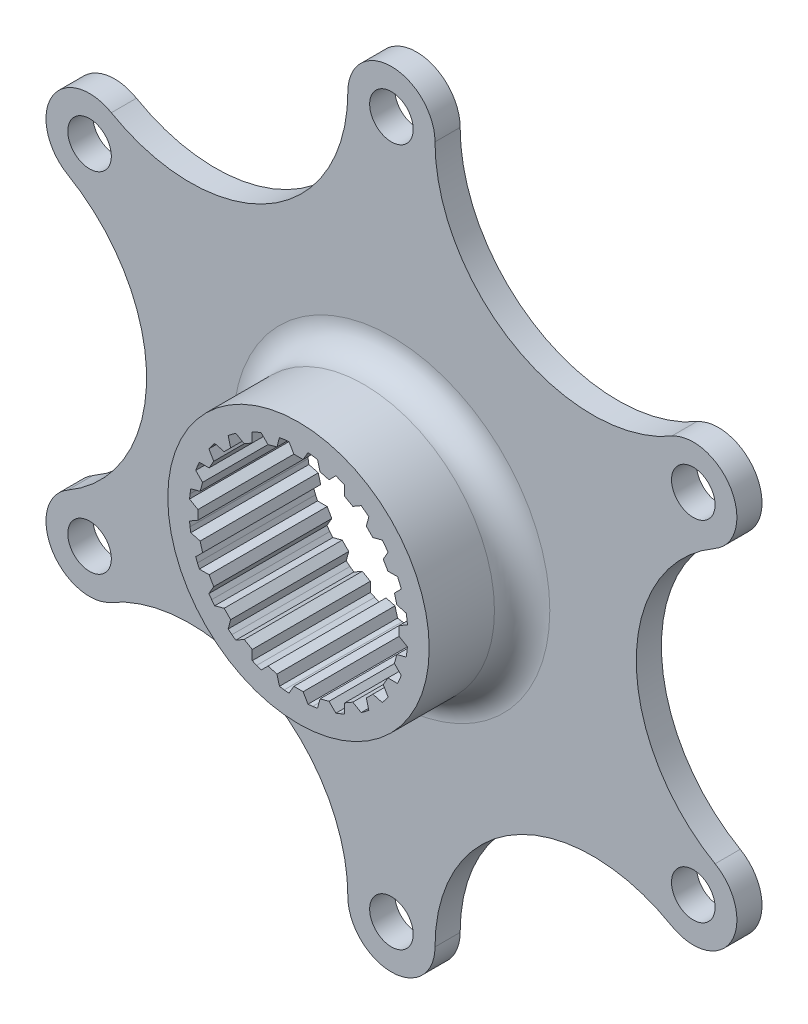
SolidWorks part; units mm, degrees
material "7075-T6 (SN)"
ref_plane "Front Plane" through (0, 0, 0) normal (0, 0, 1) x (1, 0, 0)
ref_plane "Top Plane" through (0, 0, 0) normal (0, 1, 0) x (1, 0, 0)
ref_plane "Right Plane" through (0, 0, 0) normal (1, 0, 0) x (0, 0, -1)
sketch "Sketch1" plane through (0, 0, 0) normal (0, 0, 1) x (1, 0, 0)
  circle A0 centre (0, 0) radius 115
  circle A1 centre (0, 0) radius 95
  circle A2 centre (0, 0) radius 30
  dimension "D1" = 20
  dimension "D3" = 230
extrude "Boss-Extrude1" add sketch "Sketch1" along normal mid plane 27.1 contours A0
sketch "Sketch2" plane through (0, 0, 13.55) normal (0, 0, 1) x (1, 0, 0)
  line L0 (0, 0) -> (0, 37.4359)
  line L1 (1.0655, 23.0754) -> (-1.0655, 23.0754)
  line L2 (-1.0655, 23.0754) -> (-2.1797, 25.0052)
  line L3 (-2.1797, 25.0052) -> (-2.5733, 25.0052)
  line L4 (-2.1797, 25.0052) -> (-3.2762, 24.8853)
  line L5 (1.0655, 23.0754) -> (2.1797, 25.0052)
  line L6 (-4.3664, 24.7173) -> (-3.2762, 24.8853)
  line L7 (2.1797, 25.0052) -> (3.2762, 24.8853)
  line L8 (4.3664, 24.7173) -> (3.2762, 24.8853)
  line L9 (2.1797, 25.0052) -> (3.2762, 24.8853)
  line L10 (4.3664, 24.7173) -> (3.2762, 24.8853)
  line L11 (4.9431, 22.5649) -> (4.3664, 24.7173)
  line L12 (7.0016, 22.0134) -> (4.9431, 22.5649)
  line L13 (7.0016, 22.0134) -> (8.5772, 23.589)
  line L14 (8.5772, 23.589) -> (9.6054, 23.1894)
  line L15 (10.6149, 22.745) -> (9.6054, 23.1894)
  line L16 (8.5772, 23.589) -> (9.6054, 23.1894)
  line L17 (10.6149, 22.745) -> (9.6054, 23.1894)
  line L18 (10.6149, 20.5167) -> (10.6149, 22.745)
  line L19 (12.4605, 19.4511) -> (10.6149, 20.5167)
  line L20 (12.4605, 19.4511) -> (14.3903, 20.5653)
  line L21 (14.3903, 20.5653) -> (15.2799, 19.9132)
  line L22 (16.1401, 19.2226) -> (15.2799, 19.9132)
  line L23 (14.3903, 20.5653) -> (15.2799, 19.9132)
  line L24 (16.1401, 19.2226) -> (15.2799, 19.9132)
  line L25 (15.5633, 17.0702) -> (16.1401, 19.2226)
  line L26 (17.0702, 15.5633) -> (15.5633, 17.0702)
  line L27 (17.0702, 15.5633) -> (19.2226, 16.1401)
  line L28 (19.2226, 16.1401) -> (19.9132, 15.2799)
  line L29 (20.5653, 14.3903) -> (19.9132, 15.2799)
  line L30 (19.2226, 16.1401) -> (19.9132, 15.2799)
  line L31 (20.5653, 14.3903) -> (19.9132, 15.2799)
  line L32 (19.4511, 12.4605) -> (20.5653, 14.3903)
  line L33 (20.5167, 10.6149) -> (19.4511, 12.4605)
  line L34 (20.5167, 10.6149) -> (22.745, 10.6149)
  line L35 (22.745, 10.6149) -> (23.1894, 9.6054)
  line L36 (23.589, 8.5772) -> (23.1894, 9.6054)
  line L37 (22.745, 10.6149) -> (23.1894, 9.6054)
  line L38 (23.589, 8.5772) -> (23.1894, 9.6054)
  line L39 (22.0134, 7.0016) -> (23.589, 8.5772)
  line L40 (22.5649, 4.9431) -> (22.0134, 7.0016)
  line L41 (22.5649, 4.9431) -> (24.7173, 4.3664)
  line L42 (24.7173, 4.3664) -> (24.8853, 3.2762)
  line L43 (25.0052, 2.1797) -> (24.8853, 3.2762)
  line L44 (24.7173, 4.3664) -> (24.8853, 3.2762)
  line L45 (25.0052, 2.1797) -> (24.8853, 3.2762)
  line L46 (23.0754, 1.0655) -> (25.0052, 2.1797)
  line L47 (23.0754, -1.0655) -> (23.0754, 1.0655)
  line L48 (23.0754, -1.0655) -> (25.0052, -2.1797)
  line L49 (25.0052, -2.1797) -> (24.8853, -3.2762)
  line L50 (24.7173, -4.3664) -> (24.8853, -3.2762)
  line L51 (25.0052, -2.1797) -> (24.8853, -3.2762)
  line L52 (24.7173, -4.3664) -> (24.8853, -3.2762)
  line L53 (22.5649, -4.9431) -> (24.7173, -4.3664)
  line L54 (22.0134, -7.0016) -> (22.5649, -4.9431)
  line L55 (22.0134, -7.0016) -> (23.589, -8.5772)
  line L56 (23.589, -8.5772) -> (23.1894, -9.6054)
  line L57 (22.745, -10.6149) -> (23.1894, -9.6054)
  line L58 (23.589, -8.5772) -> (23.1894, -9.6054)
  line L59 (22.745, -10.6149) -> (23.1894, -9.6054)
  line L60 (20.5167, -10.6149) -> (22.745, -10.6149)
  line L61 (19.4511, -12.4605) -> (20.5167, -10.6149)
  line L62 (19.4511, -12.4605) -> (20.5653, -14.3903)
  line L63 (20.5653, -14.3903) -> (19.9132, -15.2799)
  line L64 (19.2226, -16.1401) -> (19.9132, -15.2799)
  line L65 (20.5653, -14.3903) -> (19.9132, -15.2799)
  line L66 (19.2226, -16.1401) -> (19.9132, -15.2799)
  line L67 (17.0702, -15.5633) -> (19.2226, -16.1401)
  line L68 (15.5633, -17.0702) -> (17.0702, -15.5633)
  line L69 (15.5633, -17.0702) -> (16.1401, -19.2226)
  line L70 (16.1401, -19.2226) -> (15.2799, -19.9132)
  line L71 (14.3903, -20.5653) -> (15.2799, -19.9132)
  line L72 (16.1401, -19.2226) -> (15.2799, -19.9132)
  line L73 (14.3903, -20.5653) -> (15.2799, -19.9132)
  line L74 (12.4605, -19.4511) -> (14.3903, -20.5653)
  line L75 (10.6149, -20.5167) -> (12.4605, -19.4511)
  line L76 (10.6149, -20.5167) -> (10.6149, -22.745)
  line L77 (10.6149, -22.745) -> (9.6054, -23.1894)
  line L78 (8.5772, -23.589) -> (9.6054, -23.1894)
  line L79 (10.6149, -22.745) -> (9.6054, -23.1894)
  line L80 (8.5772, -23.589) -> (9.6054, -23.1894)
  line L81 (7.0016, -22.0134) -> (8.5772, -23.589)
  line L82 (4.9431, -22.5649) -> (7.0016, -22.0134)
  line L83 (4.9431, -22.5649) -> (4.3664, -24.7173)
  line L84 (4.3664, -24.7173) -> (3.2762, -24.8853)
  line L85 (2.1797, -25.0052) -> (3.2762, -24.8853)
  line L86 (4.3664, -24.7173) -> (3.2762, -24.8853)
  line L87 (2.1797, -25.0052) -> (3.2762, -24.8853)
  line L88 (1.0655, -23.0754) -> (2.1797, -25.0052)
  line L89 (-1.0655, -23.0754) -> (1.0655, -23.0754)
  line L90 (-1.0655, -23.0754) -> (-2.1797, -25.0052)
  line L91 (-2.1797, -25.0052) -> (-3.2762, -24.8853)
  line L92 (-4.3664, -24.7173) -> (-3.2762, -24.8853)
  line L93 (-2.1797, -25.0052) -> (-3.2762, -24.8853)
  line L94 (-4.3664, -24.7173) -> (-3.2762, -24.8853)
  line L95 (-4.9431, -22.5649) -> (-4.3664, -24.7173)
  line L96 (-7.0016, -22.0134) -> (-4.9431, -22.5649)
  line L97 (-7.0016, -22.0134) -> (-8.5772, -23.589)
  line L98 (-8.5772, -23.589) -> (-9.6054, -23.1894)
  line L99 (-10.6149, -22.745) -> (-9.6054, -23.1894)
  line L100 (-8.5772, -23.589) -> (-9.6054, -23.1894)
  line L101 (-10.6149, -22.745) -> (-9.6054, -23.1894)
  line L102 (-10.6149, -20.5167) -> (-10.6149, -22.745)
  line L103 (-12.4605, -19.4511) -> (-10.6149, -20.5167)
  line L104 (-12.4605, -19.4511) -> (-14.3903, -20.5653)
  line L105 (-14.3903, -20.5653) -> (-15.2799, -19.9132)
  line L106 (-16.1401, -19.2226) -> (-15.2799, -19.9132)
  line L107 (-14.3903, -20.5653) -> (-15.2799, -19.9132)
  line L108 (-16.1401, -19.2226) -> (-15.2799, -19.9132)
  line L109 (-15.5633, -17.0702) -> (-16.1401, -19.2226)
  line L110 (-17.0702, -15.5633) -> (-15.5633, -17.0702)
  line L111 (-17.0702, -15.5633) -> (-19.2226, -16.1401)
  line L112 (-19.2226, -16.1401) -> (-19.9132, -15.2799)
  line L113 (-20.5653, -14.3903) -> (-19.9132, -15.2799)
  line L114 (-19.2226, -16.1401) -> (-19.9132, -15.2799)
  line L115 (-20.5653, -14.3903) -> (-19.9132, -15.2799)
  line L116 (-19.4511, -12.4605) -> (-20.5653, -14.3903)
  line L117 (-20.5167, -10.6149) -> (-19.4511, -12.4605)
  line L118 (-20.5167, -10.6149) -> (-22.745, -10.6149)
  line L119 (-22.745, -10.6149) -> (-23.1894, -9.6054)
  line L120 (-23.589, -8.5772) -> (-23.1894, -9.6054)
  line L121 (-22.745, -10.6149) -> (-23.1894, -9.6054)
  line L122 (-23.589, -8.5772) -> (-23.1894, -9.6054)
  line L123 (-22.0134, -7.0016) -> (-23.589, -8.5772)
  line L124 (-22.5649, -4.9431) -> (-22.0134, -7.0016)
  line L125 (-22.5649, -4.9431) -> (-24.7173, -4.3664)
  line L126 (-24.7173, -4.3664) -> (-24.8853, -3.2762)
  line L127 (-25.0052, -2.1797) -> (-24.8853, -3.2762)
  line L128 (-24.7173, -4.3664) -> (-24.8853, -3.2762)
  line L129 (-25.0052, -2.1797) -> (-24.8853, -3.2762)
  line L130 (-23.0754, -1.0655) -> (-25.0052, -2.1797)
  line L131 (-23.0754, 1.0655) -> (-23.0754, -1.0655)
  line L132 (-23.0754, 1.0655) -> (-25.0052, 2.1797)
  line L133 (-25.0052, 2.1797) -> (-24.8853, 3.2762)
  line L134 (-24.7173, 4.3664) -> (-24.8853, 3.2762)
  line L135 (-25.0052, 2.1797) -> (-24.8853, 3.2762)
  line L136 (-24.7173, 4.3664) -> (-24.8853, 3.2762)
  line L137 (-22.5649, 4.9431) -> (-24.7173, 4.3664)
  line L138 (-22.0134, 7.0016) -> (-22.5649, 4.9431)
  line L139 (-22.0134, 7.0016) -> (-23.589, 8.5772)
  line L140 (-23.589, 8.5772) -> (-23.1894, 9.6054)
  line L141 (-22.745, 10.6149) -> (-23.1894, 9.6054)
  line L142 (-23.589, 8.5772) -> (-23.1894, 9.6054)
  line L143 (-22.745, 10.6149) -> (-23.1894, 9.6054)
  line L144 (-20.5167, 10.6149) -> (-22.745, 10.6149)
  line L145 (-19.4511, 12.4605) -> (-20.5167, 10.6149)
  line L146 (-19.4511, 12.4605) -> (-20.5653, 14.3903)
  line L147 (-20.5653, 14.3903) -> (-19.9132, 15.2799)
  line L148 (-19.2226, 16.1401) -> (-19.9132, 15.2799)
  line L149 (-20.5653, 14.3903) -> (-19.9132, 15.2799)
  line L150 (-19.2226, 16.1401) -> (-19.9132, 15.2799)
  line L151 (-17.0702, 15.5633) -> (-19.2226, 16.1401)
  line L152 (-15.5633, 17.0702) -> (-17.0702, 15.5633)
  line L153 (-15.5633, 17.0702) -> (-16.1401, 19.2226)
  line L154 (-16.1401, 19.2226) -> (-15.2799, 19.9132)
  line L155 (-14.3903, 20.5653) -> (-15.2799, 19.9132)
  line L156 (-16.1401, 19.2226) -> (-15.2799, 19.9132)
  line L157 (-14.3903, 20.5653) -> (-15.2799, 19.9132)
  line L158 (-12.4605, 19.4511) -> (-14.3903, 20.5653)
  line L159 (-10.6149, 20.5167) -> (-12.4605, 19.4511)
  line L160 (-10.6149, 20.5167) -> (-10.6149, 22.745)
  line L161 (-10.6149, 22.745) -> (-9.6054, 23.1894)
  line L162 (-8.5772, 23.589) -> (-9.6054, 23.1894)
  line L163 (-10.6149, 22.745) -> (-9.6054, 23.1894)
  line L164 (-8.5772, 23.589) -> (-9.6054, 23.1894)
  line L165 (-7.0016, 22.0134) -> (-8.5772, 23.589)
  line L166 (-4.9431, 22.5649) -> (-7.0016, 22.0134)
  line L167 (-4.9431, 22.5649) -> (-4.3664, 24.7173)
  line L168 (-4.3664, 24.7173) -> (-3.2762, 24.8853)
  line L169 (-2.1797, 25.0052) -> (-3.2762, 24.8853)
  circle A0 centre (0, 0) radius 80
  circle A1 centre (0, 0) radius 25.1 construction
  circle A2 centre (0, 0) radius 23.0754 construction
  point P13 (0, 23.0754)
  dimension "D1" = 1.0655
  dimension "D2" = 46.1508
  dimension "D3" = 50.2
  dimension "D4" = 60
  dimension "D5" = 2.2283
  dimension "D6" = 6.241
  dimension "D7" = 24
extrude "Cut-Extrude1" cut sketch "Sketch2" against normal through all contours L167 L166 L165 L162 L161 L160 L159 L158 L155 L154 L153 L152 L151 L148 L147 L146 L145 L144 L141 L140 L139 L138 L137 L134 L133 L132 L131 L130 L127 L126 L125 L124 L123 L120 L119 L118 L117 L116 L113 L112 L111 L110 L109 L106 L105 L104 L103 L102 L99 L98 L97
sketch "Sketch3" plane through (0, 0, 13.55) normal (0, 0, 1) x (1, 0, 0)
  circle A0 centre (0, 0) radius 95
  circle A2 centre (0, 0) radius 30
  circle A3 centre (0, 0) radius 95 construction
extrude "Cut-Extrude13" cut sketch "Sketch3" against normal blind 16.06
fillet "Fillet1" radius 6.35 1 edges at (30, 0, -2.51)
ref_plane "Plane1" through (0, 0, -13.55) normal (0, 0, -1) x (-1, 0, 0)
sketch "Sketch7" plane through (0, 0, -13.55) normal (0, 0, -1) x (-1, 0, 0)
  circle A0 centre (0, 0) radius 30
  circle A1 centre (0, 0) radius 95
  circle A2 centre (0, 0) radius 95 construction
extrude "Cut-Extrude14" cut sketch "Sketch7" against normal blind 5.27
fillet "Fillet2" [suppressed] radius 3.175
sketch "Sketch8" plane through (0, 0, -13.55) normal (0, 0, -1) x (-1, 0, 0)
  line L0 (0, 0) -> (-113.4958, 0)
  circle A0 centre (0, 0) radius 95
  circle A1 centre (0, 0) radius 115
  circle A3 centre (-80, 0) radius 3.97
  circle A4 centre (-40, 69.282) radius 3.97
  circle A5 centre (40, 69.282) radius 3.97
  circle A6 centre (80, 0) radius 3.97
  circle A7 centre (40, -69.282) radius 3.97
  circle A8 centre (-40, -69.282) radius 3.97
  circle A9 centre (0, 0) radius 80 construction
  circle A10 centre (0, 0) radius 115 construction
  circle A11 centre (0, 0) radius 95 construction
  dimension "D1" = 6
  dimension "D2" = 160
extrude "Cut-Extrude17" cut sketch "Sketch8" against normal through all contours A0 | A1
sketch "Sketch9" plane through (0, 0, -13.55) normal (0, 0, -1) x (-1, 0, 0)
  line L0 (0, 0) -> (0, 112.897) construction
  circle A0 centre (0, 80) radius 5
  circle A1 centre (0, 0) radius 95
  circle A2 centre (0, 0) radius 95
  circle A3 centre (69.282, 40) radius 5
  circle A4 centre (69.282, -40) radius 5
  circle A5 centre (0, -80) radius 5
  circle A6 centre (-69.282, -40) radius 5
  circle A7 centre (-69.282, 40) radius 5
  point P18 (0, 0)
  dimension "D2" = 10
  dimension "D4" = 80
  dimension "D1" = 0
  dimension "D3" = 6
extrude "Cut-Extrude20" cut sketch "Sketch9" against normal through all contours A6 | A5 | A4 | A3 | A0 | A7
sketch "Sketch10" plane through (0, 0, -13.55) normal (0, 0, -1) x (-1, 0, 0)
  line L0 (-77.9423, -45) -> (-60.6218, -35) construction
  line L1 (-74.282, -31.3397) -> (-64.282, -48.6603) construction
  line L2 (0, -90) -> (0, -70) construction
  line L3 (-10, -80) -> (10, -80) construction
  line L4 (-77.9423, 45) -> (-60.6218, 35) construction
  line L5 (-64.282, 48.6603) -> (-74.282, 31.3397) construction
  line L6 (0, 90) -> (0, 70) construction
  line L7 (10, 80) -> (-10, 80) construction
  line L8 (77.9423, 45) -> (60.6218, 35) construction
  line L9 (74.282, 31.3397) -> (64.282, 48.6603) construction
  line L10 (77.9423, -45) -> (60.6218, -35) construction
  line L11 (64.282, -48.6603) -> (74.282, -31.3397) construction
  circle A0 centre (-69.282, -40) radius 5 construction
  circle A1 centre (0, -80) radius 5 construction
  circle A2 centre (69.282, -40) radius 5 construction
  circle A3 centre (69.282, 40) radius 5 construction
  circle A4 centre (0, 80) radius 5 construction
  circle A5 centre (-69.282, 40) radius 5 construction
  circle A6 centre (-69.282, -40) radius 5
  circle A7 centre (0, -80) radius 5
  circle A8 centre (69.282, -40) radius 5
  circle A9 centre (69.282, 40) radius 5
  circle A10 centre (0, 80) radius 5
  circle A11 centre (-69.282, 40) radius 5
  circle A12 centre (-69.282, 40) radius 10
  circle A13 centre (0, 80) radius 10
  circle A14 centre (69.282, 40) radius 10
  circle A15 centre (69.282, -40) radius 10
  circle A16 centre (0, -80) radius 10
  circle A17 centre (-69.282, -40) radius 10
  arc A18 (-64.282, 48.6603) -> (-10, 80) centre (-46.188, 80) ccw
  arc A19 (10, 80) -> (64.282, 48.6603) centre (46.188, 80) ccw
  arc A20 (74.282, 31.3397) -> (74.282, -31.3397) centre (92.376, 0) ccw
  arc A21 (64.282, -48.6603) -> (10, -80) centre (46.188, -80) ccw
  arc A22 (-10, -80) -> (-64.282, -48.6603) centre (-46.188, -80) ccw
  arc A23 (-74.282, -31.3397) -> (-74.282, 31.3397) centre (-92.376, 0) ccw
  circle A24 centre (0, 0) radius 95 construction
  circle A25 centre (0, 0) radius 95
  point P50 (0, 0)
  point P68 (0, 0)
  dimension "D1" = 20
  dimension "D2" = 20
  dimension "D3" = 20
  dimension "D4" = 20
  dimension "D5" = 20
  dimension "D6" = 20
  dimension "D8" = 6
  dimension "D7" = 6
extrude "Cut-Extrude21" cut sketch "Sketch10" against normal through all
sketch "Sketch11" plane through (0, 0, -13.55) normal (0, 0, -1) x (-1, 0, 0)
  circle A0 centre (0, 0) radius 30
  circle A1 centre (0, 0) radius 30 construction
extrude "Cut-Extrude22" cut sketch "Sketch11" against normal up to surface (5.27 mm away) up to face at (-30, 0, -8.28)
sketch "Sketch13" plane through (0, 0, 13.55) normal (0, 0, 1) x (1, 0, 0)
  line L120 (1.0655, 23.0754) -> (-1.0655, 23.0754)
  line L121 (2.1797, 25.0052) -> (1.0655, 23.0754)
  line L122 (3.2762, 24.8853) -> (2.1797, 25.0052)
  line L123 (4.3664, 24.7173) -> (3.2762, 24.8853)
  line L124 (4.9431, 22.5649) -> (4.3664, 24.7173)
  line L125 (7.0016, 22.0134) -> (4.9431, 22.5649)
  line L126 (8.5772, 23.589) -> (7.0016, 22.0134)
  line L127 (9.6054, 23.1894) -> (8.5772, 23.589)
  line L128 (10.6149, 22.745) -> (9.6054, 23.1894)
  line L129 (10.6149, 20.5167) -> (10.6149, 22.745)
  line L130 (12.4605, 19.4511) -> (10.6149, 20.5167)
  line L131 (14.3903, 20.5653) -> (12.4605, 19.4511)
  line L132 (15.2799, 19.9132) -> (14.3903, 20.5653)
  line L133 (16.1401, 19.2226) -> (15.2799, 19.9132)
  line L134 (15.5633, 17.0702) -> (16.1401, 19.2226)
  line L135 (17.0702, 15.5633) -> (15.5633, 17.0702)
  line L136 (19.2226, 16.1401) -> (17.0702, 15.5633)
  line L137 (19.9132, 15.2799) -> (19.2226, 16.1401)
  line L138 (20.5653, 14.3903) -> (19.9132, 15.2799)
  line L139 (19.4511, 12.4605) -> (20.5653, 14.3903)
  line L140 (20.5167, 10.6149) -> (19.4511, 12.4605)
  line L141 (22.745, 10.6149) -> (20.5167, 10.6149)
  line L142 (23.1894, 9.6054) -> (22.745, 10.6149)
  line L143 (23.589, 8.5772) -> (23.1894, 9.6054)
  line L144 (22.0134, 7.0016) -> (23.589, 8.5772)
  line L145 (22.5649, 4.9431) -> (22.0134, 7.0016)
  line L146 (24.7173, 4.3664) -> (22.5649, 4.9431)
  line L147 (24.8853, 3.2762) -> (24.7173, 4.3664)
  line L148 (25.0052, 2.1797) -> (24.8853, 3.2762)
  line L149 (23.0754, 1.0655) -> (25.0052, 2.1797)
  line L150 (23.0754, -1.0655) -> (23.0754, 1.0655)
  line L151 (25.0052, -2.1797) -> (23.0754, -1.0655)
  line L152 (24.8853, -3.2762) -> (25.0052, -2.1797)
  line L153 (24.7173, -4.3664) -> (24.8853, -3.2762)
  line L154 (22.5649, -4.9431) -> (24.7173, -4.3664)
  line L155 (22.0134, -7.0016) -> (22.5649, -4.9431)
  line L156 (23.589, -8.5772) -> (22.0134, -7.0016)
  line L157 (23.1894, -9.6054) -> (23.589, -8.5772)
  line L158 (22.745, -10.6149) -> (23.1894, -9.6054)
  line L159 (20.5167, -10.6149) -> (22.745, -10.6149)
  line L160 (19.4511, -12.4605) -> (20.5167, -10.6149)
  line L161 (20.5653, -14.3903) -> (19.4511, -12.4605)
  line L162 (19.9132, -15.2799) -> (20.5653, -14.3903)
  line L163 (19.2226, -16.1401) -> (19.9132, -15.2799)
  line L164 (17.0702, -15.5633) -> (19.2226, -16.1401)
  line L165 (15.5633, -17.0702) -> (17.0702, -15.5633)
  line L166 (16.1401, -19.2226) -> (15.5633, -17.0702)
  line L167 (15.2799, -19.9132) -> (16.1401, -19.2226)
  line L168 (14.3903, -20.5653) -> (15.2799, -19.9132)
  line L169 (12.4605, -19.4511) -> (14.3903, -20.5653)
  line L170 (10.6149, -20.5167) -> (12.4605, -19.4511)
  line L171 (10.6149, -22.745) -> (10.6149, -20.5167)
  line L172 (9.6054, -23.1894) -> (10.6149, -22.745)
  line L173 (8.5772, -23.589) -> (9.6054, -23.1894)
  line L174 (7.0016, -22.0134) -> (8.5772, -23.589)
  line L175 (4.9431, -22.5649) -> (7.0016, -22.0134)
  line L176 (4.3664, -24.7173) -> (4.9431, -22.5649)
  line L177 (3.2762, -24.8853) -> (4.3664, -24.7173)
  line L178 (2.1797, -25.0052) -> (3.2762, -24.8853)
  line L179 (1.0655, -23.0754) -> (2.1797, -25.0052)
  line L180 (-1.0655, -23.0754) -> (1.0655, -23.0754)
  line L181 (-2.1797, -25.0052) -> (-1.0655, -23.0754)
  line L182 (-3.2762, -24.8853) -> (-2.1797, -25.0052)
  line L183 (-4.3664, -24.7173) -> (-3.2762, -24.8853)
  line L184 (-4.9431, -22.5649) -> (-4.3664, -24.7173)
  line L185 (-7.0016, -22.0134) -> (-4.9431, -22.5649)
  line L186 (-8.5772, -23.589) -> (-7.0016, -22.0134)
  line L187 (-9.6054, -23.1894) -> (-8.5772, -23.589)
  line L188 (-10.6149, -22.745) -> (-9.6054, -23.1894)
  line L189 (-10.6149, -20.5167) -> (-10.6149, -22.745)
  line L190 (-12.4605, -19.4511) -> (-10.6149, -20.5167)
  line L191 (-14.3903, -20.5653) -> (-12.4605, -19.4511)
  line L192 (-15.2799, -19.9132) -> (-14.3903, -20.5653)
  line L193 (-16.1401, -19.2226) -> (-15.2799, -19.9132)
  line L194 (-15.5633, -17.0702) -> (-16.1401, -19.2226)
  line L195 (-17.0702, -15.5633) -> (-15.5633, -17.0702)
  line L196 (-19.2226, -16.1401) -> (-17.0702, -15.5633)
  line L197 (-19.9132, -15.2799) -> (-19.2226, -16.1401)
  line L198 (-20.5653, -14.3903) -> (-19.9132, -15.2799)
  line L199 (-19.4511, -12.4605) -> (-20.5653, -14.3903)
  line L200 (-20.5167, -10.6149) -> (-19.4511, -12.4605)
  line L201 (-22.745, -10.6149) -> (-20.5167, -10.6149)
  line L202 (-23.1894, -9.6054) -> (-22.745, -10.6149)
  line L203 (-23.589, -8.5772) -> (-23.1894, -9.6054)
  line L204 (-22.0134, -7.0016) -> (-23.589, -8.5772)
  line L205 (-22.5649, -4.9431) -> (-22.0134, -7.0016)
  line L206 (-24.7173, -4.3664) -> (-22.5649, -4.9431)
  line L207 (-24.8853, -3.2762) -> (-24.7173, -4.3664)
  line L208 (-25.0052, -2.1797) -> (-24.8853, -3.2762)
  line L209 (-23.0754, -1.0655) -> (-25.0052, -2.1797)
  line L210 (-23.0754, 1.0655) -> (-23.0754, -1.0655)
  line L211 (-25.0052, 2.1797) -> (-23.0754, 1.0655)
  line L212 (-24.8853, 3.2762) -> (-25.0052, 2.1797)
  line L213 (-24.7173, 4.3664) -> (-24.8853, 3.2762)
  line L214 (-22.5649, 4.9431) -> (-24.7173, 4.3664)
  line L215 (-22.0134, 7.0016) -> (-22.5649, 4.9431)
  line L216 (-23.589, 8.5772) -> (-22.0134, 7.0016)
  line L217 (-23.1894, 9.6054) -> (-23.589, 8.5772)
  line L218 (-22.745, 10.6149) -> (-23.1894, 9.6054)
  line L219 (-20.5167, 10.6149) -> (-22.745, 10.6149)
  line L220 (-19.4511, 12.4605) -> (-20.5167, 10.6149)
  line L221 (-20.5653, 14.3903) -> (-19.4511, 12.4605)
  line L222 (-19.9132, 15.2799) -> (-20.5653, 14.3903)
  line L223 (-19.2226, 16.1401) -> (-19.9132, 15.2799)
  line L224 (-17.0702, 15.5633) -> (-19.2226, 16.1401)
  line L225 (-15.5633, 17.0702) -> (-17.0702, 15.5633)
  line L226 (-16.1401, 19.2226) -> (-15.5633, 17.0702)
  line L227 (-15.2799, 19.9132) -> (-16.1401, 19.2226)
  line L228 (-14.3903, 20.5653) -> (-15.2799, 19.9132)
  line L229 (-12.4605, 19.4511) -> (-14.3903, 20.5653)
  line L230 (-10.6149, 20.5167) -> (-12.4605, 19.4511)
  line L231 (-10.6149, 22.745) -> (-10.6149, 20.5167)
  line L232 (-9.6054, 23.1894) -> (-10.6149, 22.745)
  line L233 (-8.5772, 23.589) -> (-9.6054, 23.1894)
  line L234 (-7.0016, 22.0134) -> (-8.5772, 23.589)
  line L235 (-4.9431, 22.5649) -> (-7.0016, 22.0134)
  line L236 (-4.3664, 24.7173) -> (-4.9431, 22.5649)
  line L237 (-3.2762, 24.8853) -> (-4.3664, 24.7173)
  line L238 (-2.1797, 25.0052) -> (-3.2762, 24.8853)
  line L239 (-1.0655, 23.0754) -> (-2.1797, 25.0052)
  line L240 (1.0655, 23.0754) -> (-1.0655, 23.0754)
  line L241 (2.1797, 25.0052) -> (1.0655, 23.0754)
  line L242 (3.2762, 24.8853) -> (2.1797, 25.0052)
  line L243 (4.3664, 24.7173) -> (3.2762, 24.8853)
  line L244 (4.9431, 22.5649) -> (4.3664, 24.7173)
  line L245 (7.0016, 22.0134) -> (4.9431, 22.5649)
  line L246 (8.5772, 23.589) -> (7.0016, 22.0134)
  line L247 (9.6054, 23.1894) -> (8.5772, 23.589)
  line L248 (10.6149, 22.745) -> (9.6054, 23.1894)
  line L249 (10.6149, 20.5167) -> (10.6149, 22.745)
  line L250 (12.4605, 19.4511) -> (10.6149, 20.5167)
  line L251 (14.3903, 20.5653) -> (12.4605, 19.4511)
  line L252 (15.2799, 19.9132) -> (14.3903, 20.5653)
  line L253 (16.1401, 19.2226) -> (15.2799, 19.9132)
  line L254 (15.5633, 17.0702) -> (16.1401, 19.2226)
  line L255 (17.0702, 15.5633) -> (15.5633, 17.0702)
  line L256 (19.2226, 16.1401) -> (17.0702, 15.5633)
  line L257 (19.9132, 15.2799) -> (19.2226, 16.1401)
  line L258 (20.5653, 14.3903) -> (19.9132, 15.2799)
  line L259 (19.4511, 12.4605) -> (20.5653, 14.3903)
  line L260 (20.5167, 10.6149) -> (19.4511, 12.4605)
  line L261 (22.745, 10.6149) -> (20.5167, 10.6149)
  line L262 (23.1894, 9.6054) -> (22.745, 10.6149)
  line L263 (23.589, 8.5772) -> (23.1894, 9.6054)
  line L264 (22.0134, 7.0016) -> (23.589, 8.5772)
  line L265 (22.5649, 4.9431) -> (22.0134, 7.0016)
  line L266 (24.7173, 4.3664) -> (22.5649, 4.9431)
  line L267 (24.8853, 3.2762) -> (24.7173, 4.3664)
  line L268 (25.0052, 2.1797) -> (24.8853, 3.2762)
  line L269 (23.0754, 1.0655) -> (25.0052, 2.1797)
  line L270 (23.0754, -1.0655) -> (23.0754, 1.0655)
  line L271 (25.0052, -2.1797) -> (23.0754, -1.0655)
  line L272 (24.8853, -3.2762) -> (25.0052, -2.1797)
  line L273 (24.7173, -4.3664) -> (24.8853, -3.2762)
  line L274 (22.5649, -4.9431) -> (24.7173, -4.3664)
  line L275 (22.0134, -7.0016) -> (22.5649, -4.9431)
  line L276 (23.589, -8.5772) -> (22.0134, -7.0016)
  line L277 (23.1894, -9.6054) -> (23.589, -8.5772)
  line L278 (22.745, -10.6149) -> (23.1894, -9.6054)
  line L279 (20.5167, -10.6149) -> (22.745, -10.6149)
  line L280 (19.4511, -12.4605) -> (20.5167, -10.6149)
  line L281 (20.5653, -14.3903) -> (19.4511, -12.4605)
  line L282 (19.9132, -15.2799) -> (20.5653, -14.3903)
  line L283 (19.2226, -16.1401) -> (19.9132, -15.2799)
  line L284 (17.0702, -15.5633) -> (19.2226, -16.1401)
  line L285 (15.5633, -17.0702) -> (17.0702, -15.5633)
  line L286 (16.1401, -19.2226) -> (15.5633, -17.0702)
  line L287 (15.2799, -19.9132) -> (16.1401, -19.2226)
  line L288 (14.3903, -20.5653) -> (15.2799, -19.9132)
  line L289 (12.4605, -19.4511) -> (14.3903, -20.5653)
  line L290 (10.6149, -20.5167) -> (12.4605, -19.4511)
  line L291 (10.6149, -22.745) -> (10.6149, -20.5167)
  line L292 (9.6054, -23.1894) -> (10.6149, -22.745)
  line L293 (8.5772, -23.589) -> (9.6054, -23.1894)
  line L294 (7.0016, -22.0134) -> (8.5772, -23.589)
  line L295 (4.9431, -22.5649) -> (7.0016, -22.0134)
  line L296 (4.3664, -24.7173) -> (4.9431, -22.5649)
  line L297 (3.2762, -24.8853) -> (4.3664, -24.7173)
  line L298 (2.1797, -25.0052) -> (3.2762, -24.8853)
  line L299 (1.0655, -23.0754) -> (2.1797, -25.0052)
  line L300 (-1.0655, -23.0754) -> (1.0655, -23.0754)
  line L301 (-2.1797, -25.0052) -> (-1.0655, -23.0754)
  line L302 (-3.2762, -24.8853) -> (-2.1797, -25.0052)
  line L303 (-4.3664, -24.7173) -> (-3.2762, -24.8853)
  line L304 (-4.9431, -22.5649) -> (-4.3664, -24.7173)
  line L305 (-7.0016, -22.0134) -> (-4.9431, -22.5649)
  line L306 (-8.5772, -23.589) -> (-7.0016, -22.0134)
  line L307 (-9.6054, -23.1894) -> (-8.5772, -23.589)
  line L308 (-10.6149, -22.745) -> (-9.6054, -23.1894)
  line L309 (-10.6149, -20.5167) -> (-10.6149, -22.745)
  line L310 (-12.4605, -19.4511) -> (-10.6149, -20.5167)
  line L311 (-14.3903, -20.5653) -> (-12.4605, -19.4511)
  line L312 (-15.2799, -19.9132) -> (-14.3903, -20.5653)
  line L313 (-16.1401, -19.2226) -> (-15.2799, -19.9132)
  line L314 (-15.5633, -17.0702) -> (-16.1401, -19.2226)
  line L315 (-17.0702, -15.5633) -> (-15.5633, -17.0702)
  line L316 (-19.2226, -16.1401) -> (-17.0702, -15.5633)
  line L317 (-19.9132, -15.2799) -> (-19.2226, -16.1401)
  line L318 (-20.5653, -14.3903) -> (-19.9132, -15.2799)
  line L319 (-19.4511, -12.4605) -> (-20.5653, -14.3903)
  line L320 (-20.5167, -10.6149) -> (-19.4511, -12.4605)
  line L321 (-22.745, -10.6149) -> (-20.5167, -10.6149)
  line L322 (-23.1894, -9.6054) -> (-22.745, -10.6149)
  line L323 (-23.589, -8.5772) -> (-23.1894, -9.6054)
  line L324 (-22.0134, -7.0016) -> (-23.589, -8.5772)
  line L325 (-22.5649, -4.9431) -> (-22.0134, -7.0016)
  line L326 (-24.7173, -4.3664) -> (-22.5649, -4.9431)
  line L327 (-24.8853, -3.2762) -> (-24.7173, -4.3664)
  line L328 (-25.0052, -2.1797) -> (-24.8853, -3.2762)
  line L329 (-23.0754, -1.0655) -> (-25.0052, -2.1797)
  line L330 (-23.0754, 1.0655) -> (-23.0754, -1.0655)
  line L331 (-25.0052, 2.1797) -> (-23.0754, 1.0655)
  line L332 (-24.8853, 3.2762) -> (-25.0052, 2.1797)
  line L333 (-24.7173, 4.3664) -> (-24.8853, 3.2762)
  line L334 (-22.5649, 4.9431) -> (-24.7173, 4.3664)
  line L335 (-22.0134, 7.0016) -> (-22.5649, 4.9431)
  line L336 (-23.589, 8.5772) -> (-22.0134, 7.0016)
  line L337 (-23.1894, 9.6054) -> (-23.589, 8.5772)
  line L338 (-22.745, 10.6149) -> (-23.1894, 9.6054)
  line L339 (-20.5167, 10.6149) -> (-22.745, 10.6149)
  line L340 (-19.4511, 12.4605) -> (-20.5167, 10.6149)
  line L341 (-20.5653, 14.3903) -> (-19.4511, 12.4605)
  line L342 (-19.9132, 15.2799) -> (-20.5653, 14.3903)
  line L343 (-19.2226, 16.1401) -> (-19.9132, 15.2799)
  line L344 (-17.0702, 15.5633) -> (-19.2226, 16.1401)
  line L345 (-15.5633, 17.0702) -> (-17.0702, 15.5633)
  line L346 (-16.1401, 19.2226) -> (-15.5633, 17.0702)
  line L347 (-15.2799, 19.9132) -> (-16.1401, 19.2226)
  line L348 (-14.3903, 20.5653) -> (-15.2799, 19.9132)
  line L349 (-12.4605, 19.4511) -> (-14.3903, 20.5653)
  line L350 (-10.6149, 20.5167) -> (-12.4605, 19.4511)
  line L351 (-10.6149, 22.745) -> (-10.6149, 20.5167)
  line L352 (-9.6054, 23.1894) -> (-10.6149, 22.745)
  line L353 (-8.5772, 23.589) -> (-9.6054, 23.1894)
  line L354 (-7.0016, 22.0134) -> (-8.5772, 23.589)
  line L355 (-4.9431, 22.5649) -> (-7.0016, 22.0134)
  line L356 (-4.3664, 24.7173) -> (-4.9431, 22.5649)
  line L357 (-3.2762, 24.8853) -> (-4.3664, 24.7173)
  line L358 (-2.1797, 25.0052) -> (-3.2762, 24.8853)
  line L359 (-1.0655, 23.0754) -> (-2.1797, 25.0052)
  circle A1 centre (0, 0) radius 30
  circle A2 centre (0, 0) radius 30
  dimension "D1" = 0
  dimension "D2" = 0
extrude "Boss-Extrude2" add sketch "Sketch13" along normal blind 5.27
